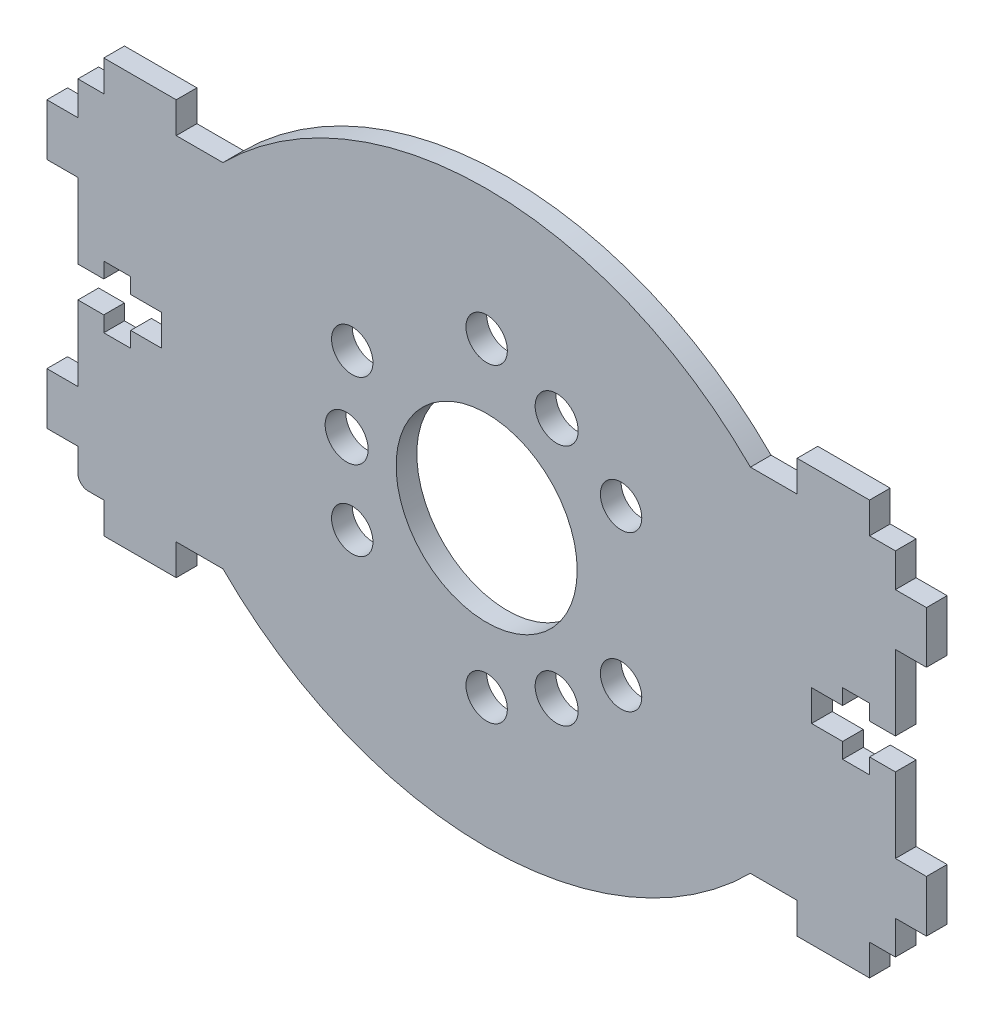
SolidWorks part; units mm, degrees
ref_plane "前视基准面" through (0, 0, 0) normal (0, 0, 1) x (1, 0, 0)
ref_plane "上视基准面" through (0, 0, 0) normal (0, 1, 0) x (1, 0, 0)
ref_plane "右视基准面" through (0, 0, 0) normal (1, 0, 0) x (0, 0, -1)
sketch "草图1" plane through (0, 0, 0) normal (0, 0, 1) x (1, 0, 0)
  line L0 (0, 0) -> (-23.3986, 0) construction
  line L2 (-39.5, -13.75) -> (-39.5, -16)
  line L143 (-42.5, -13.75) -> (-39.5, -13.75)
  line L144 (-37, 17) -> (-39.5, 17)
  line L205 (-30, 17) -> (-25.489, 17)
  line L310 (-37, 20) -> (-30, 20)
  line L325 (-30, 17) -> (-30, 20)
  line L326 (-37, 20) -> (-37, 17)
  line L337 (-39.5, 1.5) -> (-39.5, 8.75)
  line L338 (-39.5, 8.75) -> (-42.5, 8.75)
  line L340 (-42.5, 13.75) -> (-39.5, 13.75)
  line L341 (-39.5, 13.75) -> (-39.5, 17)
  line L345 (-39.5, -8.75) -> (-42.5, -8.75)
  line L346 (-39.5, -1.5) -> (-39.5, -8.75)
  line L368 (-37, -20) -> (-37, -17)
  line L369 (-30, -17) -> (-30, -20)
  line L371 (-38.5, -17) -> (-37, -17)
  line L372 (42.5, -8.75) -> (42.5, -13.75)
  line L373 (42.5, 13.75) -> (42.5, 8.75)
  line L374 (30, -17) -> (25.489, -17)
  line L375 (37, -20) -> (30, -20)
  line L376 (39.5, -17) -> (37, -17)
  line L378 (30, -17) -> (30, -20)
  line L379 (37, -20) -> (37, -17)
  line L380 (39.5, -1.5) -> (39.5, -8.75)
  line L381 (39.5, -8.75) -> (42.5, -8.75)
  line L382 (-37, -20) -> (-30, -20)
  line L383 (-30, -17) -> (-25.489, -17)
  line L384 (-42.5, 13.75) -> (-42.5, 8.75)
  line L385 (-42.5, -8.75) -> (-42.5, -13.75)
  line L386 (0, 0) -> (0, -3.3498) construction
  line L387 (39.5, 13.75) -> (39.5, 17)
  line L388 (42.5, 13.75) -> (39.5, 13.75)
  line L389 (39.5, 8.75) -> (42.5, 8.75)
  line L390 (39.5, 1.5) -> (39.5, 8.75)
  line L391 (37, 20) -> (37, 17)
  line L392 (30, 17) -> (30, 20)
  line L393 (37, 20) -> (30, 20)
  line L394 (30, 17) -> (25.489, 17)
  line L395 (37, 17) -> (39.5, 17)
  line L396 (42.5, -13.75) -> (39.5, -13.75)
  line L397 (39.5, -13.75) -> (39.5, -17)
  line L398 (-37, -1.5) -> (-37, -3)
  line L399 (-31.4, 1.5) -> (-31.4, -1.5)
  line L400 (-37, 1.5) -> (-37, 3)
  line L401 (-39.5, 1.5) -> (-37, 1.5)
  line L402 (-37, -3) -> (-34.4, -3)
  line L403 (-34.4, -3) -> (-34.4, -1.5)
  line L404 (-34.4, -1.5) -> (-31.4, -1.5)
  line L405 (-34.4, 1.5) -> (-31.4, 1.5)
  line L406 (-34.4, 3) -> (-34.4, 1.5)
  line L407 (-37, 3) -> (-34.4, 3)
  line L408 (-37, -1.5) -> (-39.5, -1.5)
  line L409 (37, -1.5) -> (39.5, -1.5)
  line L410 (37, 3) -> (34.4, 3)
  line L411 (34.4, 3) -> (34.4, 1.5)
  line L412 (34.4, 1.5) -> (31.4, 1.5)
  line L413 (34.4, -1.5) -> (31.4, -1.5)
  line L414 (34.4, -3) -> (34.4, -1.5)
  line L415 (37, -3) -> (34.4, -3)
  line L416 (39.5, 1.5) -> (37, 1.5)
  line L417 (37, 1.5) -> (37, 3)
  line L418 (31.4, 1.5) -> (31.4, -1.5)
  line L419 (37, -1.5) -> (37, -3)
  circle A13 centre (0, 0) radius 15 construction
  circle A14 centre (0, 0) radius 13.53 construction
  circle A15 centre (0, -15) radius 2
  circle A16 centre (-12.9904, -7.5) radius 2
  circle A17 centre (-12.9904, 7.5) radius 2
  circle A18 centre (0, 15) radius 2
  circle A19 centre (12.9904, 7.5) radius 2
  circle A20 centre (12.9904, -7.5) radius 2
  circle A21 centre (-13.53, 0) radius 2.08
  circle A22 centre (6.765, 11.7173) radius 2.08
  circle A23 centre (6.765, -11.7173) radius 2.08
  circle A24 centre (0, 0) radius 8.75
  arc A27 (-25.489, 17) -> (25.489, 17) centre (0, -8.489) cw
  arc A28 (-25.489, -17) -> (25.489, -17) centre (0, 8.489) ccw
  arc A29 (-38.5, -17) -> (-39.5, -16) centre (-38.5, -16) cw
  point P76 (-39.5, -17)
  dimension "D1" = 3
  dimension "D3" = 1
  dimension "D2" = 6
extrude "凸台-拉伸2" add sketch "草图1" along normal blind 2
sketch "草图2" plane through (39.5, 0, 0) normal (1, 0, 0) x (0, 0, -1)
  line L0 (-1, 1.5) -> (-1, -1.5)
  line L1 (-2, 1.5) -> (0, 1.5) construction
  line L2 (-2, -1.5) -> (0, -1.5) construction
  circle A0 centre (-1, 0) radius 1.5
sketch "草图3" plane through (-39.5, 0, 0) normal (-1, 0, 0) x (0, 0, 1)
  line L0 (1, 1.5) -> (1, -1.5)
  line L1 (2, 1.5) -> (0, 1.5) construction
  line L2 (2, -1.5) -> (0, -1.5) construction
  circle A0 centre (1, 0) radius 1.5
